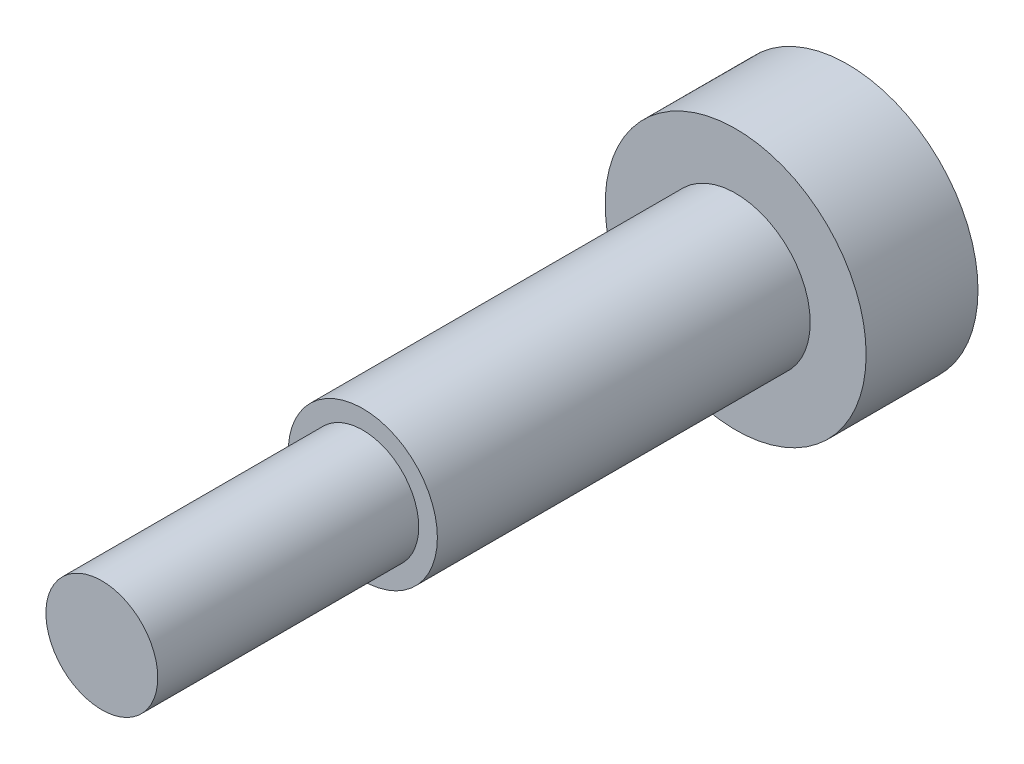
SolidWorks part; units mm, degrees
ref_plane "Front Plane" through (0, 0, 0) normal (0, 0, 1) x (1, 0, 0)
ref_plane "Top Plane" through (0, 0, 0) normal (0, 1, 0) x (1, 0, 0)
ref_plane "Right Plane" through (0, 0, 0) normal (1, 0, 0) x (0, 0, -1)
sketch "S01 - Socket head" plane through (0, 0, 0) normal (0, 0, 1) x (1, 0, 0)
  circle A0 centre (0, 0) radius 3.5
  dimension "D1" = 7
extrude "01 - Socket head" add sketch "S01 - Socket head" along normal blind 3 from offset 3
sketch "S02 - Ground shoulder" plane through (0, 0, 0) normal (0, 0, 1) x (1, 0, 0)
  circle A0 centre (0, 0) radius 2
  dimension "D1" = 4
extrude "02 - Ground shoulder" add sketch "S02 - Ground shoulder" along normal blind 10
sketch "S03 - Threaded tip major diameter" plane through (0, 0, 0) normal (0, 0, 1) x (1, 0, 0)
  circle A0 centre (0, 0) radius 1.5
  dimension "D1" = 3
extrude "03 - Threaded tip major diameter" add sketch "S03 - Threaded tip major diameter" along normal blind 7 from offset 10
sketch "S04 - Hexagonal drive" plane through (0, 0, 0) normal (0, 0, 1) x (1, 0, 0)
  line L0 (1.1547, 0) -> (0.5774, 1)
  line L1 (0.5774, 1) -> (-0.5774, 1)
  line L2 (-0.5774, 1) -> (-1.1547, 0)
  line L3 (-1.1547, 0) -> (-0.5774, -1)
  line L4 (-0.5774, -1) -> (0.5774, -1)
  line L5 (0.5774, -1) -> (1.1547, 0)
  dimension "D1" = 0.5774
  dimension "D2" = 1.1547
  dimension "D3" = 0.5774
  dimension "D4" = 1.1547
  dimension "D5" = 1
  dimension "D6" = 1
extrude "04 - Hexagonal drive" cut sketch "S04 - Hexagonal drive" along normal blind 2.14 from offset 3.1
